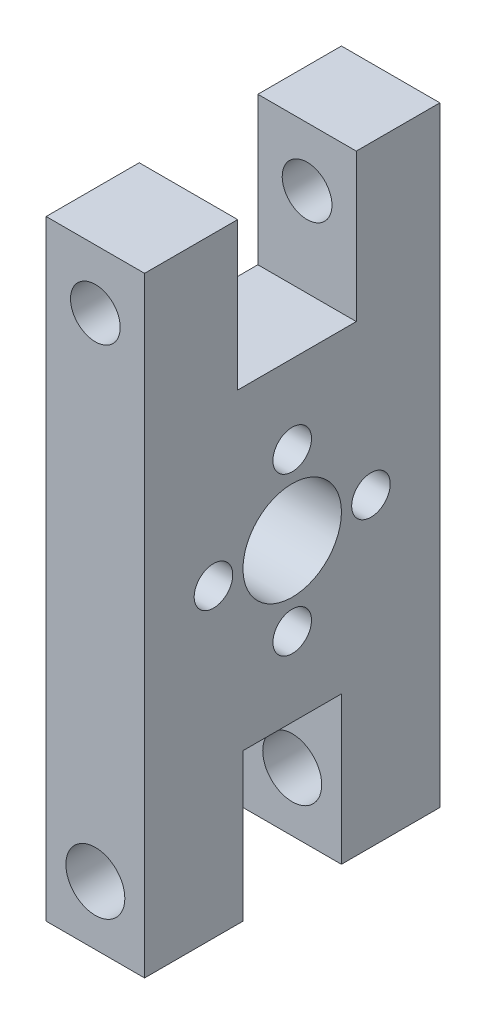
SolidWorks part; units mm, degrees
ref_plane "Alzado" through (0, 0, 0) normal (0, 0, 1) x (1, 0, 0)
ref_plane "Planta" through (0, 0, 0) normal (0, 1, 0) x (1, 0, 0)
ref_plane "Vista lateral" through (0, 0, 0) normal (1, 0, 0) x (0, 0, -1)
sketch "Croquis1" plane through (0, 0, 0) normal (1, 0, 0) x (0, 0, -1)
  line L0 (-15, 0) -> (15, 0) construction
  line L1 (15, -31) -> (5, -31)
  line L2 (15, -31) -> (15, 31)
  line L3 (15, 31) -> (6.5083, 31)
  line L4 (-15, -31) -> (-15, 31)
  line L5 (15, -31) -> (-15, 31) construction
  line L6 (15, 31) -> (-15, -31) construction
  line L7 (0, -31) -> (0, 25.9883) construction
  line L8 (-5.5421, 31) -> (-5.5421, 16)
  line L9 (-5.5421, 16) -> (6.5083, 16)
  line L10 (6.5083, 31) -> (6.5083, 16)
  line L11 (-4.4579, 35.9766) -> (6.5083, 16) construction
  line L12 (-5.5421, 16) -> (5.5421, 35.9766) construction
  line L13 (-5.5421, 31) -> (-15, 31)
  line L14 (-5, -31) -> (-15, -31)
  line L16 (-5, -31) -> (-5, -16)
  line L17 (-5, -16) -> (5, -16)
  line L18 (5, -31) -> (5, -16)
  line L19 (-5, -46) -> (5, -16) construction
  line L20 (-5, -16) -> (5, -46) construction
  circle A0 centre (0, 0) radius 5
  circle A1 centre (-8, 0) radius 1.9583
  circle A2 centre (0, 8) radius 1.9583
  circle A3 centre (8, 0) radius 1.9583
  circle A4 centre (0, -8) radius 1.9583
  point P0 (0, 0)
  point P8 (0.5153, 26.9171)
  point P34 (0, 0)
  dimension "D3" = 10
  dimension "D9" = 8
  dimension "D1" = 30
  dimension "D2" = 62
  dimension "D4" = 10
  dimension "D5" = 20
  dimension "D6" = 10
  dimension "D7" = 30
  dimension "D8" = 15
  dimension "D10" = 4
extrude "Saliente-Extruir1" add sketch "Croquis1" along normal blind 10
sketch "Croquis2" plane through (0, 0, 15) normal (0, 0, 1) x (1, 0, 0)
  line L0 (5, -31) -> (5, 31) construction
  line L1 (10, -31) -> (0, -31) construction
  line L2 (10, 31) -> (0, 31) construction
  circle A0 centre (5, 25) radius 2.5264
  circle A1 centre (5, -25) radius 2.9946
  dimension "D1" = 50
  dimension "D2" = 25
extrude "Cortar-Extruir1" cut sketch "Croquis2" against normal through all
